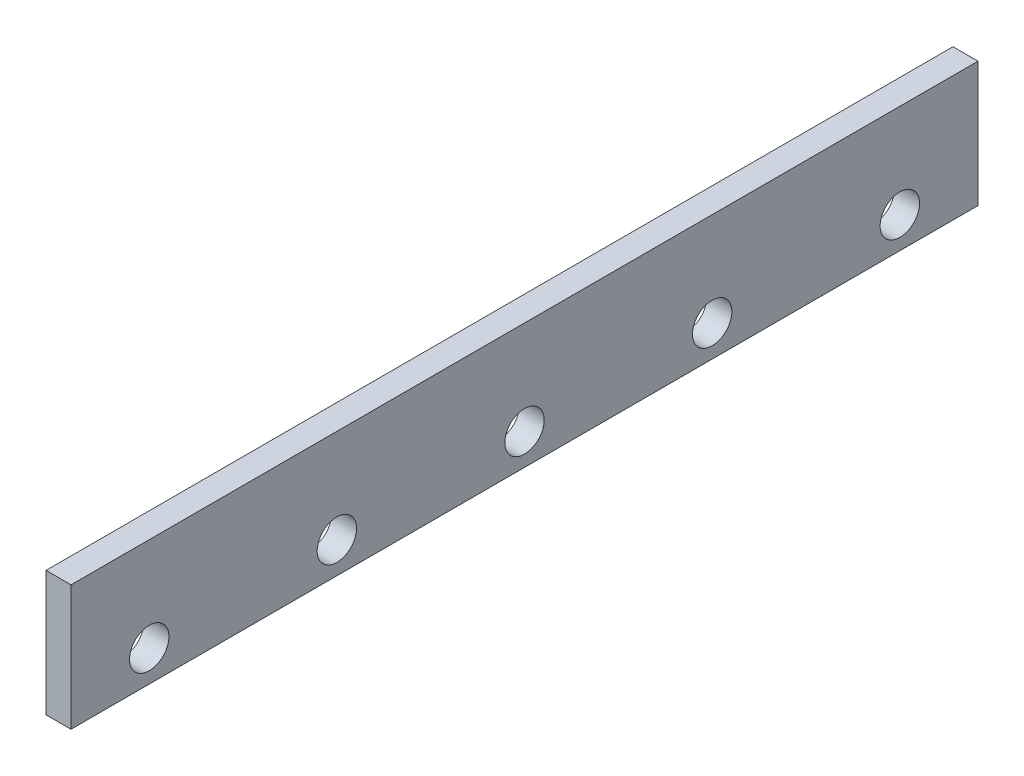
SolidWorks part; units mm, degrees
ref_plane "Alzado" through (0, 0, 0) normal (0, 0, 1) x (1, 0, 0)
ref_plane "Planta" through (0, 0, 0) normal (0, 1, 0) x (1, 0, 0)
ref_plane "Vista lateral" through (0, 0, 0) normal (1, 0, 0) x (0, 0, -1)
sketch "Croquis1" plane through (0, 0, 0) normal (1, 0, 0) x (0, 0, -1)
  line L1 (-290, 40) -> (290, 40)
  line L2 (-290, 40) -> (-290, -40)
  line L3 (-290, -40) -> (290, -40)
  line L4 (290, 40) -> (290, -40)
  line L5 (-290, 40) -> (290, -40) construction
  line L6 (-290, -40) -> (290, 40) construction
  point P0 (0, 0)
  dimension "D1" = 580
  dimension "D2" = 80
extrude "Saliente-Extruir1" add sketch "Croquis1" against normal blind 16
sketch "Croquis2" plane through (0, 0, 0) normal (1, 0, 0) x (0, 0, -1)
  line L0 (-290, 40) -> (-290, -40) construction
  line L1 (-290, -40) -> (290, -40) construction
  circle A0 centre (-240, -20) radius 12.6
  circle A1 centre (-120, -20) radius 12.6
  circle A2 centre (0, -20) radius 12.6
  circle A3 centre (120, -20) radius 12.6
  circle A4 centre (240, -20) radius 12.6
  dimension "D1" = 25.2
  dimension "D4" = 120
  dimension "D2" = 50
  dimension "D3" = 20
  dimension "D5" = 120
  dimension "D6" = 120
  dimension "D7" = 120
extrude "Cortar-Extruir1" cut sketch "Croquis2" against normal through all
